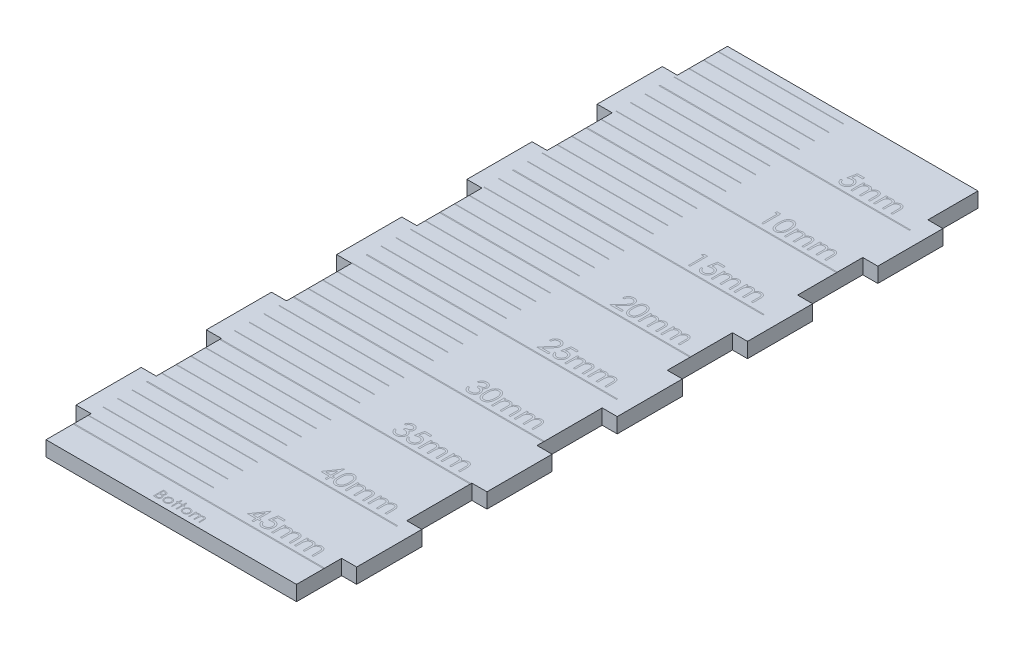
SolidWorks part; units mm, degrees
ref_plane "Front Plane" through (0, 0, 0) normal (0, 0, 1) x (1, 0, 0)
ref_plane "Top Plane" through (0, 0, 0) normal (0, 1, 0) x (1, 0, 0)
ref_plane "Right Plane" through (0, 0, 0) normal (1, 0, 0) x (0, 0, -1)
sketch "Sketch1" plane through (0, 0, 0) normal (0, 1, 0) x (1, 0, 0)
  line L0 (0, 136) -> (0, 126)
  line L1 (0, 0) -> (50, 0)
  line L2 (0, 0) -> (0, 136) construction
  line L3 (0, 136) -> (50, 136)
  line L4 (50, 0) -> (50, 136) construction
  line L5 (0, 126) -> (-3, 126)
  line L6 (-3, 126) -> (-3, 113)
  line L7 (-3, 113) -> (0, 113)
  line L8 (0, 113) -> (0, 100)
  line L9 (0, 100) -> (-3, 100)
  line L10 (-3, 100) -> (-3, 87)
  line L11 (-3, 87) -> (0, 87)
  line L12 (0, 87) -> (0, 74)
  line L13 (0, 74) -> (-3, 74)
  line L14 (-3, 74) -> (-3, 61)
  line L15 (-3, 61) -> (0, 61)
  line L16 (0, 61) -> (0, 48)
  line L17 (0, 48) -> (-3, 48)
  line L18 (-3, 48) -> (-3, 35)
  line L19 (-3, 35) -> (0, 35)
  line L20 (0, 35) -> (0, 22)
  line L21 (0, 22) -> (-3, 22)
  line L22 (-3, 22) -> (-3, 9)
  line L23 (-3, 9) -> (0, 9)
  line L24 (0, 9) -> (0, 0)
  line L25 (25, 136) -> (25, 0) construction
  line L26 (50, 9) -> (50, 0)
  line L27 (53, 9) -> (50, 9)
  line L28 (53, 22) -> (53, 9)
  line L29 (50, 22) -> (53, 22)
  line L30 (50, 35) -> (50, 22)
  line L31 (53, 35) -> (50, 35)
  line L32 (53, 48) -> (53, 35)
  line L33 (50, 48) -> (53, 48)
  line L34 (50, 61) -> (50, 48)
  line L35 (53, 61) -> (50, 61)
  line L36 (53, 74) -> (53, 61)
  line L37 (50, 74) -> (53, 74)
  line L38 (50, 87) -> (50, 74)
  line L39 (53, 87) -> (50, 87)
  line L40 (53, 100) -> (53, 87)
  line L41 (50, 100) -> (53, 100)
  line L42 (50, 113) -> (50, 100)
  line L43 (53, 113) -> (50, 113)
  line L44 (53, 126) -> (53, 113)
  line L45 (50, 126) -> (53, 126)
  line L46 (50, 136) -> (50, 126)
  dimension "D1" = 50
  dimension "D2" = 136
  dimension "D3" = 10
  dimension "D4" = 13
  dimension "D5" = 3
extrude "Boss-Extrude1" add sketch "Sketch1" along normal blind 3
sketch "Sketch3" plane through (0, 3, 0) normal (0, 1, 0) x (1, 0, 0)
  line L0 (0, 1) -> (50, 1) construction
  line L1 (0, 9) -> (0, 0) construction
  line L2 (50, 0) -> (50, 9) construction
  line L3 (0, 0) -> (50, 0) construction
  text T0 "Bottom" font "Century Gothic" height 2
  dimension "D1" = 1
split line "Split Line1"
sketch3d "3DSketch1"
  line L0 (0, 3, 0) -> (0, 3, -136) construction
  line L1 (0, -61.0895, -112.6733) -> (0, 3, -136) construction
  line L2 (0, -38.9385, -120.7356) -> (0, 3, -5.5106) construction
  line L3 (0, -29.5416, -124.1558) -> (0, 3, -34.7487) construction
  line L4 (0, -34.24, -122.4457) -> (0, 3, -20.1296) construction
  line L5 (0, -24.8431, -125.8659) -> (0, 3, -49.3677) construction
  line L6 (0, -20.1446, -127.576) -> (0, 3, -63.9867) construction
  line L7 (0, -15.4462, -129.2861) -> (0, 3, -78.6057) construction
  line L8 (0, -10.7477, -130.9962) -> (0, 3, -93.2247) construction
  line L9 (0, -6.0492, -132.7063) -> (0, 3, -107.8438) construction
  line L10 (0, -1.3508, -134.4164) -> (0, 3, -122.4628) construction
  line L11 (0, 3, -122.4628) -> (50, 3, -122.4628)
  line L12 (0, 3, -107.8438) -> (50, 3, -107.8438)
  line L13 (0, 3, -93.2247) -> (50, 3, -93.2247)
  line L14 (0, 3, -78.6057) -> (50, 3, -78.6057)
  line L15 (0, 3, -5.5106) -> (50, 3, -5.5106)
  line L16 (0, 3, -20.1296) -> (50, 3, -20.1296)
  line L17 (0, 3, -34.7487) -> (50, 3, -34.7487)
  line L18 (0, 3, -49.3677) -> (50, 3, -49.3677)
  line L19 (0, 3, -63.9867) -> (50, 3, -63.9867)
  line L20 (50, 3, -136) -> (50, 3, 0) construction
  line L21 (50, 3, -126) -> (50, 3, -136) construction
  line L22 (0, 3, 0) -> (0, 3, -136) construction
  dimension "D11" = 4.63
  dimension "D2" = 70
  dimension "D3" = 5
  dimension "D4" = 5
  dimension "D5" = 5
  dimension "D6" = 5
  dimension "D7" = 5
  dimension "D8" = 5
  dimension "D9" = 5
  dimension "D10" = 5
sketch "Sketch4" plane through (0, 3, 0) normal (0, 1, 0) x (1, 0, 0)
  line L0 (0, 122.4457) -> (50, 122.4457) construction
  line L1 (0, 107.8438) -> (50, 107.8438) construction
  line L2 (0, 93.2247) -> (50, 93.2247) construction
  line L3 (0, 78.6057) -> (50, 78.6057) construction
  line L4 (0, 78.6057) -> (50, 78.6057) construction
  line L5 (50, 136) -> (50, 0) construction
  line L6 (0, 63.9867) -> (50, 63.9867) construction
  line L7 (0, 49.3677) -> (50, 49.3677) construction
  line L8 (0, 34.7487) -> (50, 34.7487) construction
  line L9 (50, 20.1296) -> (0, 20.1296) construction
  line L10 (0, 5.5106) -> (50, 5.5106) construction
  line L11 (0, 5.5106) -> (50, 5.5106) construction
  line L12 (50, 123.4457) -> (29.9803, 123.4457) construction
  line L13 (50, 108.8438) -> (29.9803, 108.8438) construction
  line L14 (50, 94.2247) -> (29.9803, 94.2247) construction
  line L15 (50, 79.6057) -> (29.9803, 79.6057) construction
  line L16 (50, 64.9867) -> (29.9803, 64.9867) construction
  line L17 (50, 50.3677) -> (29.9803, 50.3677) construction
  line L18 (50, 35.7487) -> (29.9803, 35.7487) construction
  line L19 (50, 21.1296) -> (29.9803, 21.1296) construction
  line L20 (50, 6.5106) -> (29.9803, 6.5106) construction
  line L22 (29.9803, 123.4457) -> (29.9803, 6.5106) construction
  line L23 (25, 5.5106) -> (25, 8.4344) construction
  line L24 (25, 8.4344) -> (0, 8.4344) construction
  line L25 (0, 0) -> (0, 136) construction
  line L26 (25, 8.4344) -> (25, 11.3582) construction
  line L27 (25, 11.3582) -> (0, 11.3582) construction
  line L28 (25, 11.3582) -> (25, 14.282) construction
  line L29 (25, 14.282) -> (0, 14.282) construction
  line L30 (25, 14.282) -> (25, 17.2058) construction
  line L31 (25, 17.2058) -> (0, 17.2058) construction
  line L32 (25, 17.2058) -> (25, 20.1296) construction
  line L33 (25, 20.1296) -> (25, 23.0534) construction
  line L34 (25, 23.0534) -> (0, 23.0534) construction
  line L35 (25, 23.0534) -> (25, 25.9772) construction
  line L36 (25, 25.9772) -> (0, 25.9772) construction
  line L37 (25, 25.9772) -> (25, 28.901) construction
  line L38 (25, 28.901) -> (0, 28.901) construction
  line L39 (25, 28.901) -> (25, 31.8248) construction
  line L40 (25, 31.8248) -> (0, 31.8248) construction
  line L41 (25, 31.8248) -> (25, 34.7487) construction
  line L42 (25, 34.7487) -> (25, 37.6725) construction
  line L43 (25, 37.6725) -> (0, 37.6725) construction
  line L44 (25, 37.6725) -> (25, 40.5963) construction
  line L45 (25, 40.5963) -> (0, 40.5963) construction
  line L46 (25, 40.5963) -> (25, 43.5201) construction
  line L47 (25, 43.5201) -> (0, 43.5201) construction
  line L48 (25, 43.5201) -> (25, 46.4439) construction
  line L49 (25, 46.4439) -> (0, 46.4439) construction
  line L50 (25, 46.4439) -> (25, 49.3677) construction
  line L51 (0, 49.3677) -> (50, 49.3677) construction
  line L52 (25, 49.3677) -> (25, 52.2915) construction
  line L53 (25, 52.2915) -> (0, 52.2915) construction
  line L54 (25, 52.2915) -> (25, 55.2153) construction
  line L55 (25, 55.2153) -> (0, 55.2153) construction
  line L56 (25, 55.2153) -> (25, 58.1391) construction
  line L57 (25, 58.1391) -> (0, 58.1391) construction
  line L58 (25, 58.1391) -> (25, 61.0629) construction
  line L59 (25, 61.0629) -> (0, 61.0629) construction
  line L60 (25, 61.0629) -> (25, 63.9867) construction
  line L61 (0, 63.9867) -> (50, 63.9867) construction
  line L62 (25, 63.9867) -> (25, 66.9105) construction
  line L63 (25, 66.9105) -> (0, 66.9105) construction
  line L64 (25, 66.9105) -> (25, 69.8343) construction
  line L65 (25, 69.8343) -> (0, 69.8343) construction
  line L66 (25, 69.8343) -> (25, 72.7581) construction
  line L67 (25, 72.7581) -> (0, 72.7581) construction
  line L68 (25, 72.7581) -> (25, 75.6819) construction
  line L69 (25, 75.6819) -> (0, 75.6819) construction
  line L70 (25, 75.6819) -> (25, 78.6057) construction
  line L71 (25, 78.6057) -> (25, 81.5295) construction
  line L72 (25, 81.5295) -> (0, 81.5295) construction
  line L73 (25, 81.5295) -> (25, 84.4533) construction
  line L74 (25, 84.4533) -> (0, 84.4533) construction
  line L75 (25, 84.4533) -> (25, 87.3771) construction
  line L76 (25, 87.3771) -> (0, 87.3771) construction
  line L77 (25, 87.3771) -> (25, 90.3009) construction
  line L78 (25, 90.3009) -> (0, 90.3009) construction
  line L79 (25, 90.3009) -> (25, 93.2247) construction
  line L80 (0, 93.2247) -> (50, 93.2247) construction
  line L81 (25, 93.2247) -> (25, 96.1485) construction
  line L82 (25, 96.1485) -> (0, 96.1485) construction
  line L83 (25, 96.1485) -> (25, 99.0724) construction
  line L84 (25, 99.0724) -> (0, 99.0724) construction
  line L85 (25, 99.0724) -> (25, 101.9962) construction
  line L86 (25, 101.9962) -> (0, 101.9962) construction
  line L87 (25, 101.9962) -> (25, 104.92) construction
  line L88 (25, 104.92) -> (0, 104.92) construction
  line L89 (25, 104.92) -> (25, 107.8438) construction
  line L90 (0, 107.8438) -> (50, 107.8438) construction
  line L91 (25, 107.8438) -> (25, 110.7676) construction
  line L92 (25, 110.7676) -> (0, 110.7676) construction
  line L93 (25, 110.7676) -> (25, 113.6914) construction
  line L94 (25, 113.6914) -> (0, 113.6914) construction
  line L95 (25, 113.6914) -> (25, 116.6152) construction
  line L96 (25, 116.6152) -> (0, 116.6152) construction
  line L97 (25, 116.6152) -> (25, 119.539) construction
  line L98 (25, 119.539) -> (0, 119.539) construction
  line L99 (25, 119.539) -> (25, 122.4628) construction
  line L100 (0, 122.4628) -> (50, 122.4628) construction
  line L101 (25, 122.4628) -> (25, 125.3866) construction
  line L102 (25, 125.3866) -> (0, 125.3866) construction
  line L103 (25, 125.3866) -> (25, 128.3104) construction
  line L104 (25, 128.3104) -> (0, 128.3104) construction
  line L105 (25, 128.3104) -> (25, 131.2342) construction
  line L106 (25, 131.2342) -> (0, 131.2342) construction
  line L107 (25, 131.2342) -> (25, 134.158) construction
  line L108 (25, 134.158) -> (0, 134.158) construction
  line L109 (25, 134.158) -> (25, 137.0818) construction
  line L110 (25, 8.4844) -> (0, 8.4844)
  line L111 (25, 11.4082) -> (0, 11.4082)
  line L112 (25, 14.332) -> (0, 14.332)
  line L113 (25, 17.2558) -> (0, 17.2558)
  line L114 (25, 23.1034) -> (0, 23.1034)
  line L115 (25, 26.0272) -> (0, 26.0272)
  line L116 (25, 28.951) -> (0, 28.951)
  line L117 (25, 31.8748) -> (0, 31.8748)
  line L118 (25, 37.7225) -> (0, 37.7225)
  line L119 (25, 40.6463) -> (0, 40.6463)
  line L120 (25, 43.5701) -> (0, 43.5701)
  line L121 (25, 46.4939) -> (0, 46.4939)
  line L122 (25, 52.3415) -> (0, 52.3415)
  line L123 (25, 55.2653) -> (0, 55.2653)
  line L124 (25, 58.1891) -> (0, 58.1891)
  line L125 (25, 61.1129) -> (0, 61.1129)
  line L126 (25, 66.9605) -> (0, 66.9605)
  line L127 (25, 69.8843) -> (0, 69.8843)
  line L128 (25, 72.8081) -> (0, 72.8081)
  line L129 (25, 75.7319) -> (0, 75.7319)
  line L130 (25, 81.5795) -> (0, 81.5795)
  line L131 (25, 84.5033) -> (0, 84.5033)
  line L132 (25, 87.4271) -> (0, 87.4271)
  line L133 (25, 90.3509) -> (0, 90.3509)
  line L134 (25, 96.1985) -> (0, 96.1985)
  line L135 (25, 99.1224) -> (0, 99.1224)
  line L136 (25, 102.0462) -> (0, 102.0462)
  line L137 (25, 104.97) -> (0, 104.97)
  line L138 (25, 110.8176) -> (0, 110.8176)
  line L139 (25, 113.7414) -> (0, 113.7414)
  line L140 (25, 116.6652) -> (0, 116.6652)
  line L141 (25, 119.589) -> (0, 119.589)
  line L142 (25, 125.4366) -> (0, 125.4366)
  line L143 (25, 128.3604) -> (0, 128.3604)
  line L144 (25, 131.2842) -> (0, 131.2842)
  line L145 (25, 134.208) -> (0, 134.208)
  line L146 (25, 8.3844) -> (0, 8.3844)
  line L147 (25, 11.3082) -> (0, 11.3082)
  line L148 (25, 14.232) -> (0, 14.232)
  line L149 (25, 17.1558) -> (0, 17.1558)
  line L150 (25, 23.0034) -> (0, 23.0034)
  line L151 (25, 25.9272) -> (0, 25.9272)
  line L152 (25, 28.851) -> (0, 28.851)
  line L153 (25, 31.7748) -> (0, 31.7748)
  line L154 (25, 37.6225) -> (0, 37.6225)
  line L155 (25, 40.5463) -> (0, 40.5463)
  line L156 (25, 43.4701) -> (0, 43.4701)
  line L157 (25, 46.3939) -> (0, 46.3939)
  line L158 (25, 52.2415) -> (0, 52.2415)
  line L159 (25, 55.1653) -> (0, 55.1653)
  line L160 (25, 58.0891) -> (0, 58.0891)
  line L161 (25, 61.0129) -> (0, 61.0129)
  line L162 (25, 66.8605) -> (0, 66.8605)
  line L163 (25, 69.7843) -> (0, 69.7843)
  line L164 (25, 72.7081) -> (0, 72.7081)
  line L165 (25, 75.6319) -> (0, 75.6319)
  line L166 (25, 81.4795) -> (0, 81.4795)
  line L167 (25, 84.4033) -> (0, 84.4033)
  line L168 (25, 87.3271) -> (0, 87.3271)
  line L169 (25, 90.2509) -> (0, 90.2509)
  line L170 (25, 96.0985) -> (0, 96.0985)
  line L171 (25, 99.0224) -> (0, 99.0224)
  line L172 (25, 101.9462) -> (0, 101.9462)
  line L173 (25, 104.87) -> (0, 104.87)
  line L174 (25, 110.7176) -> (0, 110.7176)
  line L175 (25, 113.6414) -> (0, 113.6414)
  line L176 (25, 116.5652) -> (0, 116.5652)
  line L177 (25, 119.489) -> (0, 119.489)
  line L178 (25, 125.3366) -> (0, 125.3366)
  line L179 (25, 128.2604) -> (0, 128.2604)
  line L180 (25, 131.1842) -> (0, 131.1842)
  line L181 (25, 134.108) -> (0, 134.108)
  line L182 (25, 8.4844) -> (25, 8.3844)
  line L183 (0, 8.4844) -> (0, 8.3844)
  line L184 (25, 11.4082) -> (25, 11.3082)
  line L185 (0, 11.4082) -> (0, 11.3082)
  line L186 (25, 14.332) -> (25, 14.232)
  line L187 (0, 14.332) -> (0, 14.232)
  line L188 (25, 17.2558) -> (25, 17.1558)
  line L189 (0, 17.2558) -> (0, 17.1558)
  line L190 (25, 23.1034) -> (25, 23.0034)
  line L191 (0, 23.1034) -> (0, 23.0034)
  line L192 (25, 26.0272) -> (25, 25.9272)
  line L193 (0, 26.0272) -> (0, 25.9272)
  line L194 (25, 28.951) -> (25, 28.851)
  line L195 (0, 28.951) -> (0, 28.851)
  line L196 (25, 31.8748) -> (25, 31.7748)
  line L197 (0, 31.8748) -> (0, 31.7748)
  line L198 (25, 37.7225) -> (25, 37.6225)
  line L199 (0, 37.7225) -> (0, 37.6225)
  line L200 (25, 40.6463) -> (25, 40.5463)
  line L201 (0, 40.6463) -> (0, 40.5463)
  line L202 (25, 43.5701) -> (25, 43.4701)
  line L203 (0, 43.5701) -> (0, 43.4701)
  line L204 (25, 46.4939) -> (25, 46.3939)
  line L205 (0, 46.4939) -> (0, 46.3939)
  line L206 (25, 52.3415) -> (25, 52.2415)
  line L207 (0, 52.3415) -> (0, 52.2415)
  line L208 (25, 55.2653) -> (25, 55.1653)
  line L209 (0, 55.2653) -> (0, 55.1653)
  line L210 (25, 58.1891) -> (25, 58.0891)
  line L211 (0, 58.1891) -> (0, 58.0891)
  line L212 (25, 61.1129) -> (25, 61.0129)
  line L213 (0, 61.1129) -> (0, 61.0129)
  line L214 (25, 66.9605) -> (25, 66.8605)
  line L215 (0, 66.9605) -> (0, 66.8605)
  line L216 (25, 69.8843) -> (25, 69.7843)
  line L217 (0, 69.8843) -> (0, 69.7843)
  line L218 (25, 72.8081) -> (25, 72.7081)
  line L219 (0, 72.8081) -> (0, 72.7081)
  line L220 (25, 75.7319) -> (25, 75.6319)
  line L221 (0, 75.7319) -> (0, 75.6319)
  line L222 (25, 81.5795) -> (25, 81.4795)
  line L223 (0, 81.5795) -> (0, 81.4795)
  line L224 (25, 84.5033) -> (25, 84.4033)
  line L225 (0, 84.5033) -> (0, 84.4033)
  line L226 (25, 87.4271) -> (25, 87.3271)
  line L227 (0, 87.4271) -> (0, 87.3271)
  line L228 (25, 90.3509) -> (25, 90.2509)
  line L229 (0, 90.3509) -> (0, 90.2509)
  line L230 (25, 96.1985) -> (25, 96.0985)
  line L231 (0, 96.1985) -> (0, 96.0985)
  line L232 (25, 99.1224) -> (25, 99.0224)
  line L233 (0, 99.1224) -> (0, 99.0224)
  line L234 (25, 102.0462) -> (25, 101.9462)
  line L235 (0, 102.0462) -> (0, 101.9462)
  line L236 (25, 104.97) -> (25, 104.87)
  line L237 (0, 104.97) -> (0, 104.87)
  line L238 (25, 110.8176) -> (25, 110.7176)
  line L239 (0, 110.8176) -> (0, 110.7176)
  line L240 (25, 113.7414) -> (25, 113.6414)
  line L241 (0, 113.7414) -> (0, 113.6414)
  line L242 (25, 116.6652) -> (25, 116.5652)
  line L243 (0, 116.6652) -> (0, 116.5652)
  line L244 (25, 119.589) -> (25, 119.489)
  line L245 (0, 119.589) -> (0, 119.489)
  line L246 (25, 125.4366) -> (25, 125.3366)
  line L247 (0, 125.4366) -> (0, 125.3366)
  line L248 (25, 128.3604) -> (25, 128.2604)
  line L249 (0, 128.3604) -> (0, 128.2604)
  line L250 (25, 131.2842) -> (25, 131.1842)
  line L251 (0, 131.2842) -> (0, 131.1842)
  line L252 (25, 134.208) -> (25, 134.108)
  line L253 (0, 134.208) -> (0, 134.108)
  line L254 (0, 122.3457) -> (50, 122.3457)
  line L255 (0, 107.7438) -> (50, 107.7438)
  line L256 (0, 93.1247) -> (50, 93.1247)
  line L257 (0, 78.5057) -> (50, 78.5057)
  line L258 (0, 63.8867) -> (50, 63.8867)
  line L259 (0, 49.2677) -> (50, 49.2677)
  line L260 (0, 34.6487) -> (50, 34.6487)
  line L261 (50, 20.2296) -> (0, 20.2296)
  line L262 (0, 5.4106) -> (50, 5.4106)
  line L263 (0, 122.5457) -> (50, 122.5457)
  line L264 (0, 107.9438) -> (50, 107.9438)
  line L265 (0, 93.3247) -> (50, 93.3247)
  line L266 (0, 78.7057) -> (50, 78.7057)
  line L267 (0, 64.0867) -> (50, 64.0867)
  line L268 (0, 49.4677) -> (50, 49.4677)
  line L269 (0, 34.8487) -> (50, 34.8487)
  line L270 (50, 20.0296) -> (0, 20.0296)
  line L271 (0, 5.6106) -> (50, 5.6106)
  line L272 (0, 122.3457) -> (0, 122.5457)
  line L273 (50, 122.3457) -> (50, 122.5457)
  line L274 (0, 107.7438) -> (0, 107.9438)
  line L275 (50, 107.7438) -> (50, 107.9438)
  line L276 (0, 93.1247) -> (0, 93.3247)
  line L277 (50, 93.1247) -> (50, 93.3247)
  line L278 (0, 78.5057) -> (0, 78.7057)
  line L279 (50, 78.5057) -> (50, 78.7057)
  line L280 (0, 63.8867) -> (0, 64.0867)
  line L281 (50, 63.8867) -> (50, 64.0867)
  line L282 (0, 49.2677) -> (0, 49.4677)
  line L283 (50, 49.2677) -> (50, 49.4677)
  line L284 (0, 34.6487) -> (0, 34.8487)
  line L285 (50, 34.6487) -> (50, 34.8487)
  line L286 (50, 20.2296) -> (50, 20.0296)
  line L287 (0, 20.2296) -> (0, 20.0296)
  line L288 (0, 5.4106) -> (0, 5.6106)
  line L289 (50, 5.4106) -> (50, 5.6106)
  text T0 "5mm"
  text T1 "10mm\r\n"
  text T2 "15mm"
  text T3 "20mm"
  text T4 "25mm"
  text T5 "30mm"
  text T6 "35mm"
  text T7 "40mm"
  text T8 "45mm"
  dimension "D1" = 1
  dimension "D2" = 1
  dimension "D3" = 1
  dimension "D4" = 1
  dimension "D5" = 1
  dimension "D6" = 1
  dimension "D7" = 1
  dimension "D8" = 1
  dimension "D9" = 1
  dimension "D10" = 0.05
  dimension "D11" = 0.05
  dimension "D12" = 0.1
  dimension "D13" = 0.1
split line "Split Line2"
